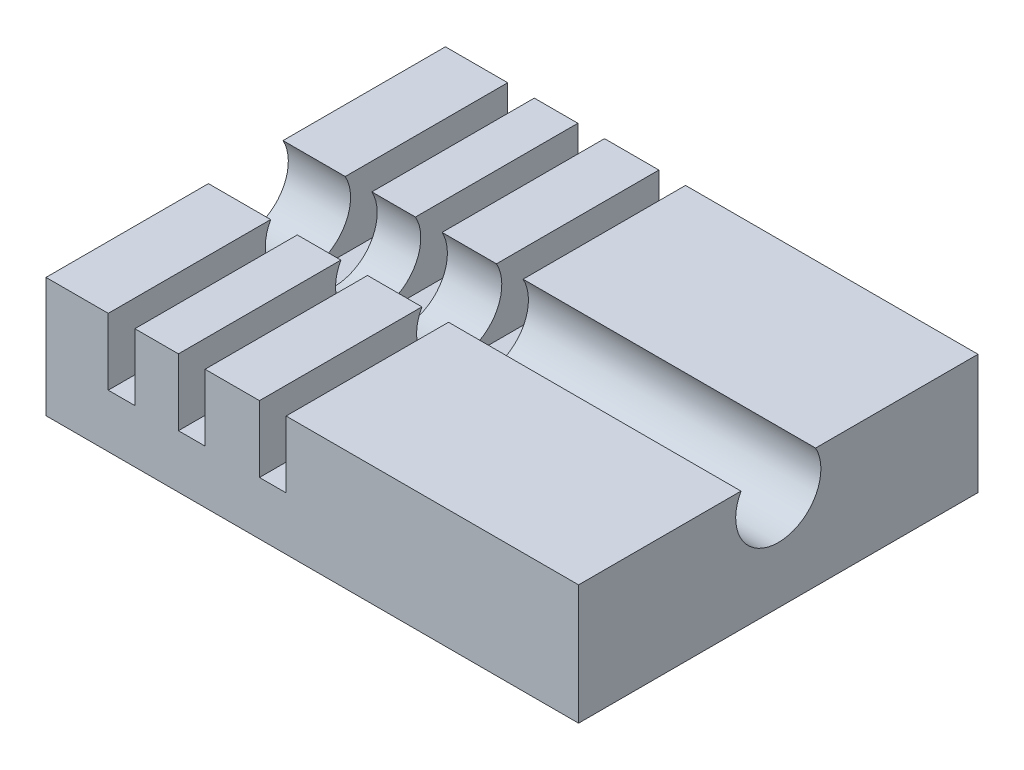
SolidWorks part; units mm, degrees
ref_plane "Front Plane" through (0, 0, 0) normal (0, 0, 1) x (1, 0, 0)
ref_plane "Top Plane" through (0, 0, 0) normal (0, 1, 0) x (1, 0, 0)
ref_plane "Right Plane" through (0, 0, 0) normal (1, 0, 0) x (0, 0, -1)
sketch "Sketch1" plane through (0, 0, 0) normal (0, 1, 0) x (1, 0, 0)
  line L1 (-10, 7.5) -> (10, 7.5)
  line L2 (-10, 7.5) -> (-10, -7.5)
  line L3 (-10, -7.5) -> (10, -7.5)
  line L4 (10, 7.5) -> (10, -7.5)
  line L5 (-10, 7.5) -> (10, -7.5) construction
  line L6 (-10, -7.5) -> (10, 7.5) construction
  point P0 (0, 0)
extrude "Boss-Extrude1" add sketch "Sketch1" along normal blind 4.5
sketch "Sketch3" plane through (10, 0, 0) normal (1, 0, 0) x (0, 0, -1)
  circle A0 centre (0, 3.7261) radius 1.6
extrude "Cut-Extrude1" cut sketch "Sketch3" against normal blind 20
sketch "Sketch4" plane through (0, 4.5, 0) normal (0, 1, 0) x (1, 0, 0)
  line L0 (10, 7.5) -> (-10, 7.5) construction
  line L1 (-7.6624, 7.5) -> (-6.6624, 7.5)
  line L2 (-7.6624, 7.5) -> (-7.6624, -7.5)
  line L3 (-7.6624, -7.5) -> (-6.6624, -7.5)
  line L4 (-6.6624, 7.5) -> (-6.6624, -7.5)
  line L5 (-10, -7.5) -> (10, -7.5) construction
extrude "Cut-Extrude2" cut sketch "Sketch4" against normal blind 2.5
sketch "Sketch5" plane through (0, 4.5, 0) normal (0, 1, 0) x (1, 0, 0)
  line L0 (-6.6624, -7.5) -> (10, -7.5) construction
  line L1 (-5.0262, -7.5) -> (-4.0262, -7.5)
  line L2 (-5.0262, -7.5) -> (-5.0262, 7.5)
  line L3 (-5.0262, 7.5) -> (-4.0262, 7.5)
  line L4 (-4.0262, -7.5) -> (-4.0262, 7.5)
  line L5 (10, 7.5) -> (-6.6624, 7.5) construction
extrude "Cut-Extrude3" cut sketch "Sketch5" against normal blind 2.5
sketch "Sketch6" plane through (0, 4.5, 0) normal (0, 1, 0) x (1, 0, 0)
  line L0 (-4.0262, -7.5) -> (10, -7.5) construction
  line L1 (-1.9834, -7.5) -> (-0.9834, -7.5)
  line L2 (-1.9834, -7.5) -> (-1.9834, 7.5)
  line L3 (-1.9834, 7.5) -> (-0.9834, 7.5)
  line L4 (-0.9834, -7.5) -> (-0.9834, 7.5)
  line L5 (10, 7.5) -> (-4.0262, 7.5) construction
extrude "Cut-Extrude5" cut sketch "Sketch6" against normal blind 2.5
